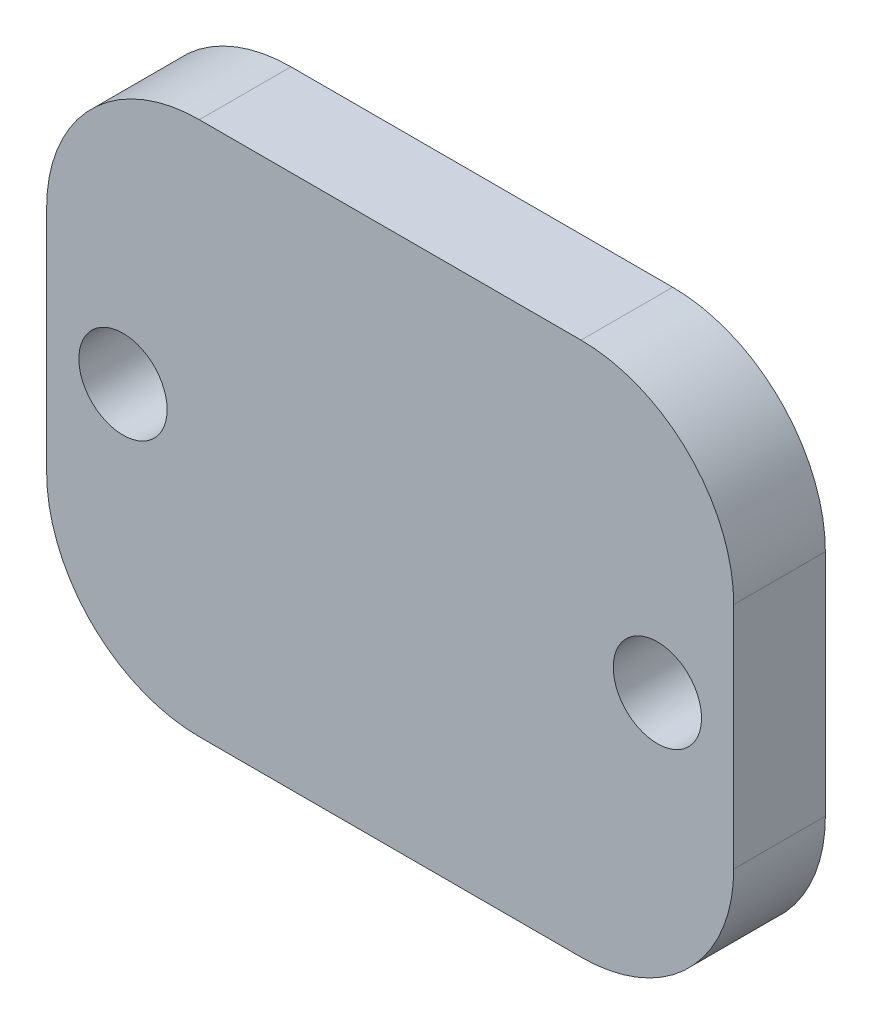
SolidWorks part; units mm, degrees
ref_plane "Front Plane" through (0, 0, 0) normal (0, 0, 1) x (1, 0, 0)
ref_plane "Top Plane" through (0, 0, 0) normal (0, 1, 0) x (1, 0, 0)
ref_plane "Right Plane" through (0, 0, 0) normal (1, 0, 0) x (0, 0, -1)
sketch "Sketch2" plane through (0, 0, 0) normal (0, 0, 1) x (1, 0, 0)
  line L0 (-121.901, 7.4753) -> (-121.901, 45.0123) construction
  line L1 (-134.401, 43.7017) -> (-109.401, 43.7017)
  line L2 (-144.401, 33.7017) -> (-144.401, 18.7017)
  line L3 (-134.401, 8.7017) -> (-109.401, 8.7017)
  line L4 (-99.401, 33.7017) -> (-99.401, 18.7017)
  line L5 (-144.401, 26.2017) -> (-96.5397, 26.2017) construction
  circle A0 centre (-139.4009, 26.2017) radius 2.89
  circle A1 centre (-104.401, 26.2017) radius 2.89
  arc A2 (-99.401, 18.7017) -> (-109.401, 8.7017) centre (-109.401, 18.7017) cw
  arc A3 (-134.401, 8.7017) -> (-144.401, 18.7017) centre (-134.401, 18.7017) cw
  arc A4 (-134.401, 43.7017) -> (-144.401, 33.7017) centre (-134.401, 33.7017) ccw
  arc A5 (-109.401, 43.7017) -> (-99.401, 33.7017) centre (-109.401, 33.7017) cw
  dimension "D4" = 10
  dimension "D5" = 10
  dimension "D1" = 45
  dimension "D2" = 35
  dimension "D3" = 22.5
extrude "Boss-Extrude1" add sketch "Sketch2" along normal blind 6
